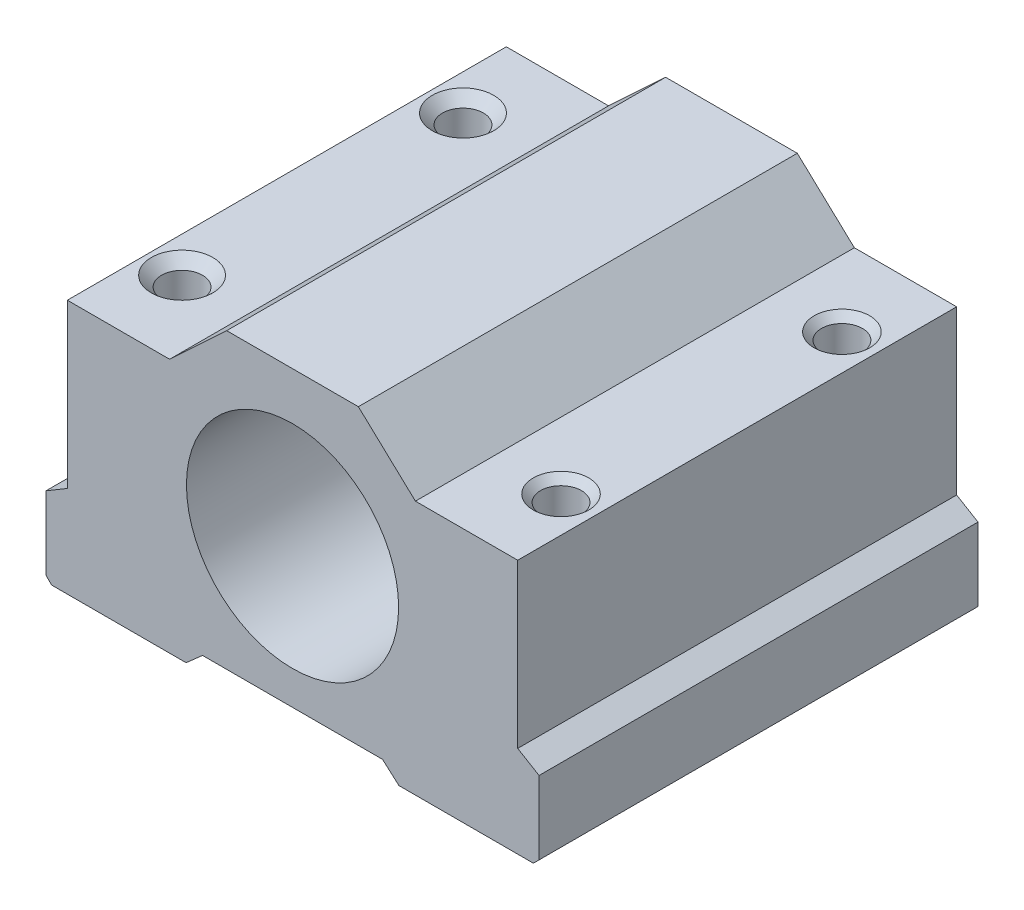
SolidWorks part; units mm, degrees
ref_plane "Alzado" through (0, 0, 0) normal (0, 0, 1) x (1, 0, 0)
ref_plane "Planta" through (0, 0, 0) normal (0, 1, 0) x (1, 0, 0)
ref_plane "Vista lateral" through (0, 0, 0) normal (1, 0, 0) x (0, 0, -1)
sketch "Croquis1" plane through (0, 0, 0) normal (0, 0, 1) x (1, 0, 0)
  line L0 (0, 0) -> (0, 20.05) construction
  line L1 (-15.39, 16.4078) -> (-15.39, 5.2676)
  line L2 (15.39, 16.4078) -> (15.39, 5.2676)
  line L3 (-15.39, 16.4078) -> (-8.4, 16.4078)
  line L4 (15.39, 16.4078) -> (8.4, 16.4078)
  line L5 (-8.4, 16.4078) -> (-4.5, 20.05)
  line L6 (-4.5, 20.05) -> (4.5, 20.05)
  line L7 (8.4, 16.4078) -> (4.5, 20.05)
  line L9 (-7.275, -0.9922) -> (-6.15, 0)
  line L12 (7.275, -0.9922) -> (6.15, 0)
  line L13 (-6.15, 0) -> (6.15, 0)
  line L14 (-15.39, 5.2676) -> (-16.85, 4.3968)
  line L15 (-16.85, 4.3968) -> (-16.85, -0.6032)
  line L19 (15.39, 5.2676) -> (16.85, 4.3968)
  line L20 (-16.4611, -0.9922) -> (-7.275, -0.9922)
  line L22 (-16.85, -0.6032) -> (-16.4611, -0.9922)
  line L23 (16.4611, -0.9922) -> (7.275, -0.9922)
  line L24 (16.85, -0.6032) -> (16.4611, -0.9922)
  line L25 (16.85, 4.3968) -> (16.85, -0.6032)
  circle A0 centre (0, 9.55) radius 7.25
  point P5 (0, 2.3)
  point P6 (0, 16.8)
  point P16 (0, 0)
  point P21 (0, 0)
  point P27 (-18.6238, 1.6074)
  point P28 (-7.5324, 0)
  point P29 (-15.39, 8.2622)
  point P30 (-15.39, 7.8442)
  point P31 (-16.85, 6.8476)
  point P32 (-15.39, 7.1145)
  point P33 (-16.4611, 0.9097)
  point P34 (0, 0)
  point P35 (-6.125, 1.9769)
  point P36 (7.0507, 0)
  point P37 (-15.39, 6.0334)
  point P38 (0, 0)
  dimension "D1" = 14.5
  dimension "D2" = 2.3
  dimension "D3" = 3.25
  dimension "D4" = 30.78
  dimension "D5" = 16.8
  dimension "D6" = 9
  dimension "D7" = 45
  dimension "D8" = 12.3
  dimension "D9" = 0.55
  dimension "D10" = 33.7
  dimension "D11" = 1.7
  dimension "D12" = 5
  dimension "D13" = 17.4
  dimension "D14" = 1.5
  dimension "D15" = 14.55
extrude "Saliente-Extruir1" add sketch "Croquis1" against normal blind 30 contours L23 L12 L13 L9 L20 L22 L15 L14 L1 L3 L5 L6 L7 L4 L2 L19 L25 L24 | A0
sketch "Croquis2" plane through (0, -0.9922, 0) normal (0, -1, 0) x (1, 0, 0)
  line L0 (-16.4611, -15) -> (-7.275, -15) construction
  line L1 (-16.4611, -30) -> (-16.4611, 0) construction
  line L2 (-7.275, -30) -> (-7.275, 0) construction
  line L3 (-16.85, -30) -> (-16.85, 0) construction
  line L4 (-16.4611, 0) -> (-7.275, 0) construction
  line L5 (0, 0) -> (0, -30) construction
  line L6 (-6.15, -30) -> (6.15, -30) construction
  circle A3 centre (-12.95, -5.4) radius 1.4
  circle A4 centre (-12.95, -24.6) radius 1.4
  circle A5 centre (12.95, -24.6) radius 1.4
  circle A6 centre (12.95, -5.4) radius 1.4
  point P7 (-14.35, -5.4)
  point P9 (-12.95, -4)
  dimension "D1" = 2.8
  dimension "D2" = 2.5
  dimension "D3" = 4
extrude "Cortar-Extruir1" cut sketch "Croquis2" against normal through all
sketch "Croquis3" plane through (0, -0.9922, 0) normal (0, -1, 0) x (1, 0, 0)
  line L0 (-16.4611, -15) -> (-7.275, -15) construction
  line L1 (-16.4611, -30) -> (-16.4611, 0) construction
  line L2 (-7.275, -30) -> (-7.275, 0) construction
  line L3 (0, 0) -> (0, -30) construction
  line L4 (-6.15, -30) -> (6.15, -30) construction
  circle A0 centre (-12.95, -5.4) radius 2.25
  circle A1 centre (-12.95, -24.6) radius 2.25
  circle A2 centre (12.95, -24.6) radius 2.25
  circle A3 centre (12.95, -5.4) radius 2.25
  dimension "D1" = 4.5
chamfer "Chaflán2" distance 0.85 angle 45 4 edges at (14.35, -0.9922, -24.6) (11.55, -0.9922, -5.4) (-11.55, -0.9922, -5.4) (-14.35, -0.9922, -24.6)
chamfer "Chaflán3" distance 0.7 angle 45 2 edges at (-12.95, 16.4078, -26) (-12.95, 16.4078, -6.8)
chamfer "Chaflán4" distance 0.5 angle 45 2 edges at (12.95, 16.4078, -4) (12.95, 16.4078, -23.2)
